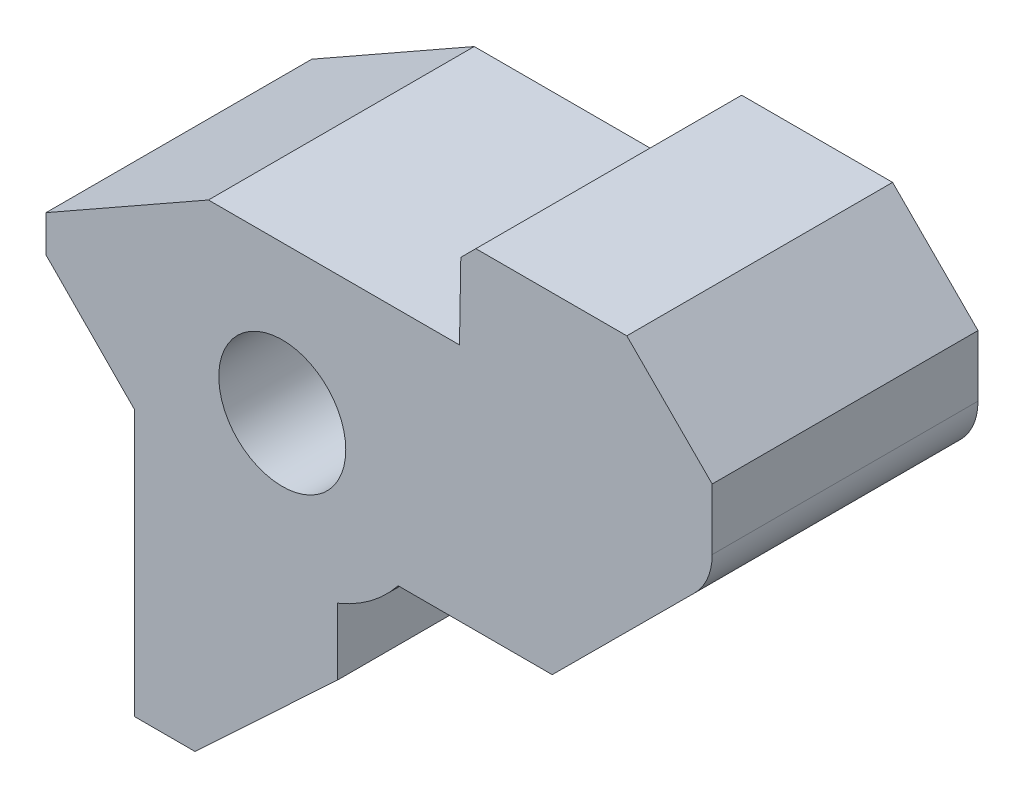
SolidWorks part; units mm, degrees
ref_plane "정면" through (0, 0, 0) normal (0, 0, 1) x (1, 0, 0)
ref_plane "윗면" through (0, 0, 0) normal (0, 1, 0) x (1, 0, 0)
ref_plane "우측면" through (0, 0, 0) normal (1, 0, 0) x (0, 0, -1)
sketch "스케치1" plane through (0, 0, 0) normal (0, 0, 1) x (1, 0, 0)
  line L0 (-5, -2.4) -> (-8, 0.6383)
  line L1 (6, 5) -> (6.0541, 8.1)
  line L2 (6.0541, 8.1) -> (11.6662, 8.1)
  line L3 (11.6662, 8.1) -> (14.5571, 5.2)
  line L4 (14.5571, 5.2) -> (14.5571, 2.3)
  line L5 (14.5571, 2.3) -> (9.1401, -3.1)
  line L6 (9.1401, -3.1) -> (3.923, -3.1)
  line L7 (1.8761, -4.6347) -> (1.8761, -6.8875)
  line L8 (-2.9568, -11.4) -> (-5, -11.4)
  line L9 (-5, -11.4) -> (-5, -2.4)
  line L10 (-2.9568, -11.4) -> (1.8761, -6.8875)
  line L11 (6, 5) -> (-2.5, 5)
  line L13 (-8, 0.6383) -> (-8, 1.8789)
  line L14 (-8, 1.8789) -> (-2.5, 5)
  circle A0 centre (0, 0) radius 2.15
  circle A1 centre (0, 0) radius 5
  dimension "D1" = 4.3
  dimension "D2" = 10
  dimension "D3" = 43.036
  dimension "D4" = 9
  dimension "D5" = 5
  dimension "D6" = 5.2
  dimension "D7" = 3.1
  dimension "D8" = 91
  dimension "D9" = 3.1
  dimension "D10" = 5.4
  dimension "D11" = 2.5
  dimension "D12" = 8
  dimension "D13" = 8.5
  dimension "D14" = 2.4
extrude "보스-돌출1" add sketch "스케치1" along normal mid plane 9
fillet "필렛1" radius 2 1 edges at (14.5571, 2.3, 0)
chamfer "모따기1" distance 0.5 angle 45 1 edges at (6.0541, 8.1, 0)
